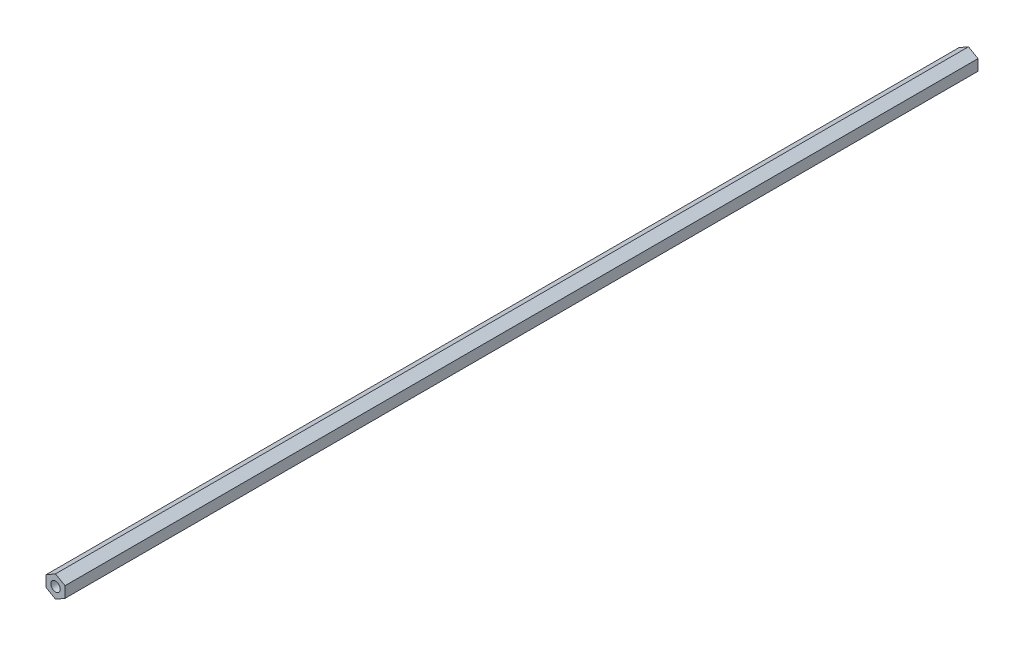
SolidWorks part; units mm, degrees
ref_plane "Front Plane" through (0, 0, 0) normal (0, 0, 1) x (1, 0, 0)
ref_plane "Top Plane" through (0, 0, 0) normal (0, 1, 0) x (1, 0, 0)
ref_plane "Right Plane" through (0, 0, 0) normal (1, 0, 0) x (0, 0, -1)
sketch "Sketch1" plane through (0, 0, 0) normal (0, 0, 1) x (1, 0, 0)
  line L1 (0, 7.3323) -> (-6.35, 3.6662) construction
  line L2 (-6.35, 3.6662) -> (-6.35, -3.6662) construction
  line L3 (-6.35, -3.6662) -> (0, -7.3323) construction
  line L4 (0, -7.3323) -> (6.35, -3.6662) construction
  line L5 (6.35, -3.6662) -> (6.35, 3.6662) construction
  line L6 (6.35, 3.6662) -> (0, 7.3323) construction
  circle A2 centre (0, 0) radius 6.35 construction
  dimension "Width" = 12.7
sketch "Sketch2" plane through (0, 0, 0) normal (1, 0, 0) x (0, 0, -1)
  line L0 (-304.8, 7.3323) -> (304.8, 7.3323) construction
  point P2 (0, 7.3323)
  point P3 (273.05, 7.3323)
  point P4 (-273.05, 7.3323)
  dimension "Length" = 609.6
  dimension "D2" = 31.75
  dimension "D1" = 31.75
sketch "Sketch3" plane through (0, 0, 0) normal (0, 0, 1) x (1, 0, 0)
  line L0 (-6.35, -3.6662) -> (0, -7.3323) construction
  line L1 (0, -7.3323) -> (6.35, -3.6662) construction
  line L2 (6.35, -3.6662) -> (6.35, 3.6662) construction
  line L3 (6.35, 3.6662) -> (0, 7.3323) construction
  line L4 (0, 7.3323) -> (-6.35, 3.6662) construction
  line L5 (-6.35, 3.6662) -> (-6.35, -3.6662) construction
  line L6 (-6.35, -3.6662) -> (0, -7.3323)
  line L7 (0, -7.3323) -> (6.35, -3.6662)
  line L8 (6.35, -3.6662) -> (6.35, 3.6662)
  line L9 (6.35, 3.6662) -> (0, 7.3323)
  line L10 (0, 7.3323) -> (-6.35, 3.6662)
  line L11 (-6.35, 3.6662) -> (-6.35, -3.6662)
extrude "Boss-Extrude2" add sketch "Sketch3" along normal up to vertex (304.8 mm away) and the other way up to vertex (304.8 mm away) up to point (0, 7.3323, 304.8) other way up to point (0, 7.3323, -304.8)
sketch "Sketch4" plane through (0, 0, 304.8) normal (0, 0, 1) x (1, 0, 0)
  point P0 (0, 0)
hole_wizard "1/4 (0.25) Diameter Hole1" positions "Sketch5" profile "Sketch6" hole size "1/4" standard "ANSI Inch"
sketch "Sketch5" plane through (0, 0, 304.8) normal (0, 0, 1) x (1, 0, 0)
  point P0 (0, 0)
sketch "Sketch6" plane through (0, 0, 304.8) normal (1, 0, 0) x (0, -1, 0)
  line L0 (0, 0) -> (0, 27.3077)
  line L1 (0, 27.3077) -> (3.175, 25.4)
  line L2 (3.175, 25.4) -> (3.175, 0)
  line L5 (3.175, 0) -> (0, 0)
  line L10 (0, 27.3077) -> (-3.175, 25.4) construction
  line L11 (0, -6.35) -> (0, 107.95) construction
  dimension "Hole Dia." = 6.35
  dimension "Hole Depth" = 25.4
  dimension "Drill Angle" = 118
hole_wizard "1/4 (0.25) Diameter Hole2" positions "Sketch7" profile "Sketch8" hole size "1/4" standard "ANSI Inch"
sketch "Sketch7" plane through (0, 0, -304.8) normal (0, 0, -1) x (-1, 0, 0)
  point P0 (0, 0)
sketch "Sketch8" plane through (0, 0, -304.8) normal (1, 0, 0) x (0, 1, 0)
  line L0 (0, 0) -> (0, 27.3077)
  line L1 (0, 27.3077) -> (3.175, 25.4)
  line L2 (3.175, 25.4) -> (3.175, 0)
  line L5 (3.175, 0) -> (0, 0)
  line L10 (0, 27.3077) -> (-3.175, 25.4) construction
  line L11 (0, -6.35) -> (0, 107.95) construction
  dimension "Hole Dia." = 6.35
  dimension "Hole Depth" = 25.4
  dimension "Drill Angle" = 118
equation "\"D2@Sketch2\" = \"D1@Sketch2\""
equation "\"D1@Sketch2\" = \"Width@Sketch1\" * 2.5"
